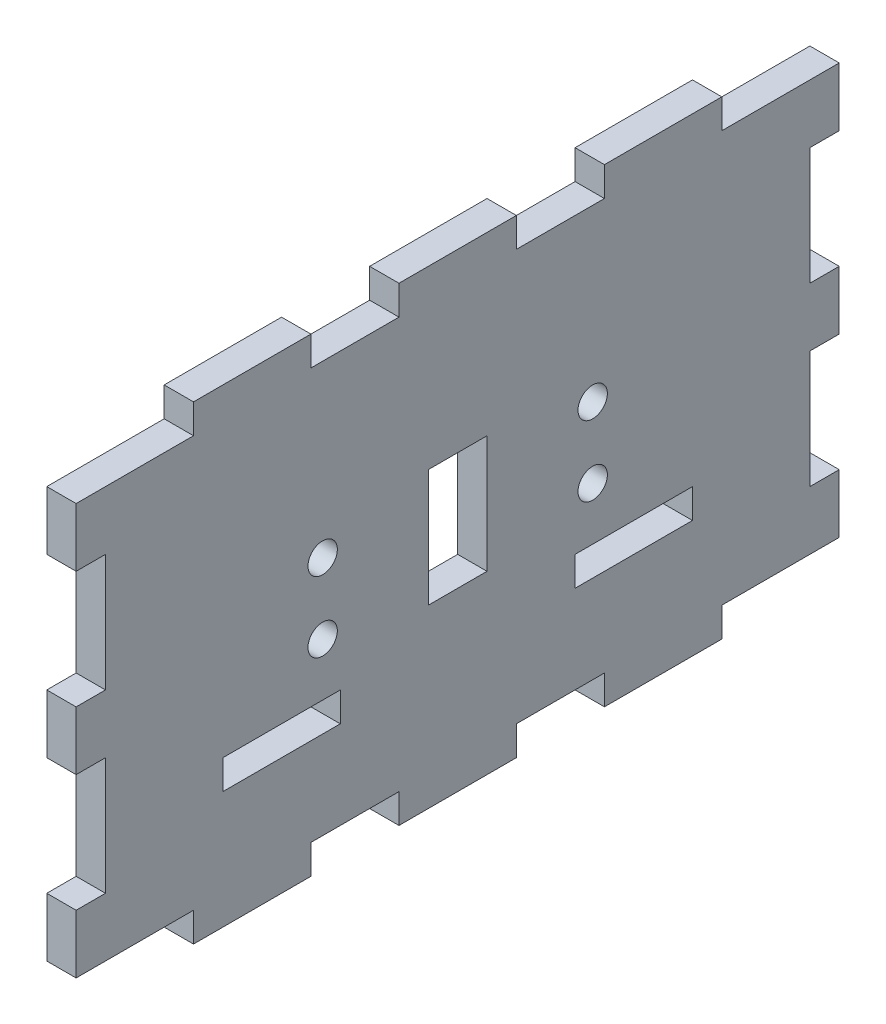
SolidWorks part; units mm, degrees
ref_plane "Front Plane" through (0, 0, 0) normal (0, 0, 1) x (1, 0, 0)
ref_plane "Top Plane" through (0, 0, 0) normal (0, 1, 0) x (1, 0, 0)
ref_plane "Right Plane" through (0, 0, 0) normal (1, 0, 0) x (0, 0, -1)
sketch "Sketch1" plane through (0, 0, 0) normal (1, 0, 0) x (0, 0, -1)
  line L0 (-109.8871, 0) -> (84.0492, 0) construction
  line L1 (0, 64.1388) -> (0, -100.6158) construction
  line L2 (-60, 35) -> (-45, 35)
  line L3 (-60, 35) -> (60, 35) construction
  line L4 (-60, 35) -> (-60, -35) construction
  line L5 (-60, -35) -> (60, -35) construction
  line L6 (60, 35) -> (60, -35) construction
  line L7 (-60, 35) -> (60, -35) construction
  line L8 (-60, -35) -> (60, 35) construction
  line L9 (-45, 35) -> (-45, 40)
  line L10 (-45, 40) -> (-25, 40)
  line L11 (-25, 40) -> (-25, 35)
  line L12 (-10, 35) -> (-10, 40)
  line L13 (-10, 40) -> (10, 40)
  line L14 (10, 40) -> (10, 35)
  line L15 (-25, 35) -> (-10, 35)
  line L16 (25, 35) -> (25, 40)
  line L17 (25, 40) -> (45, 40)
  line L18 (45, 40) -> (45, 35)
  line L19 (10, 35) -> (25, 35)
  line L20 (45, -35) -> (60, -35)
  line L21 (10, -35) -> (25, -35)
  line L22 (45, -40) -> (45, -35)
  line L23 (45, 35) -> (60, 35)
  line L24 (60, 40) -> (80, 40) [skipped]
  line L25 (80, 40) -> (80, 35) [skipped]
  line L26 (60, 35) -> (60, 40) [skipped]
  line L27 (25, -40) -> (45, -40)
  line L28 (25, -35) -> (25, -40)
  line L29 (-25, -35) -> (-10, -35)
  line L30 (10, -40) -> (10, -35)
  line L31 (-10, -40) -> (10, -40)
  line L32 (-10, -35) -> (-10, -40)
  line L33 (-25, -40) -> (-25, -35)
  line L34 (-45, -40) -> (-25, -40)
  line L35 (-45, -35) -> (-45, -40)
  line L36 (-60, -35) -> (-45, -35)
  line L37 (-60, 35) -> (-65, 35)
  line L38 (-65, 35) -> (-65, 25)
  line L39 (-65, 25) -> (-60, 25)
  line L40 (-60, 25) -> (-60, 5)
  line L41 (-60, 5) -> (-65, 5)
  line L42 (-65, 5) -> (-65, -5)
  line L43 (-65, -5) -> (-60, -5)
  line L44 (-60, -5) -> (-60, -25)
  line L45 (-60, -25) -> (-65, -25)
  line L46 (-65, -25) -> (-65, -35)
  line L47 (-65, -35) -> (-60, -35)
  line L48 (65, -35) -> (60, -35)
  line L49 (60, 35) -> (65, 35)
  line L50 (65, -25) -> (65, -35)
  line L51 (60, -25) -> (65, -25)
  line L52 (60, -5) -> (60, -25)
  line L53 (65, -5) -> (60, -5)
  line L54 (65, 5) -> (65, -5)
  line L55 (60, 5) -> (65, 5)
  line L56 (60, 25) -> (60, 5)
  line L57 (65, 25) -> (60, 25)
  line L58 (65, 35) -> (65, 25)
  point P5 (0, 0)
  dimension "D1" = 70
  dimension "D2" = 120
  dimension "D3" = 4
extrude "Boss-Extrude1" add sketch "Sketch1" along normal blind 5 contours L58 L49 L23 L18 L17 L16 L19 L14 L13 L12 L15 L11 L10 L9 L2 L37 L38 L39 L40 L41 L42 L43 L44 L45 L46 L47 L36 L35 L34 L33 L29 L32 L31 L30 L21 L28 L27 L22 L20 L48 L50 L51 L52 L53 L54 L55 L56 L57
sketch "Sketch2" plane through (0, 0, 0) normal (1, 0, 0) x (0, 0, -1)
  line L0 (0, 0) -> (39.3291, 0) construction
  line L1 (-5, 10) -> (5, 10)
  line L2 (-5, 10) -> (-5, -10)
  line L3 (-5, -10) -> (5, -10)
  line L4 (5, 10) -> (5, -10)
  line L5 (-5, 10) -> (5, -10) construction
  line L6 (-5, -10) -> (5, 10) construction
  line L7 (0, 0) -> (-48.4922, 0) construction
  line L8 (0, 17.5211) -> (0, -27.1046) construction
  circle A0 centre (23, 6) radius 2.5
  circle A1 centre (23, -6) radius 2.5
  circle A2 centre (-23, -6) radius 2.5
  circle A3 centre (-23, 6) radius 2.5
  point P0 (0, 0)
  dimension "D3" = 5
  dimension "D1" = 20
  dimension "D2" = 10
  dimension "D4" = 6
  dimension "D5" = 18
extrude "Cut-Extrude1" cut sketch "Sketch2" along normal up to surface (5 mm away) up to face at (5, 0, 0)
sketch "Sketch3" plane through (5, 0, 0) normal (1, 0, 0) x (0, 0, -1)
  line L0 (-60, -5) -> (-60, -25) construction
  line L1 (-60, -20) -> (60, -20) construction
  line L2 (60, -5) -> (60, -25) construction
  line L3 (-25, -35) -> (-10, -35) construction
  line L4 (0, -3.8143) -> (0, -32.5252) construction
  line L5 (20, -20) -> (20, -15)
  line L6 (20, -15) -> (40, -15)
  line L7 (40, -15) -> (40, -20)
  line L8 (40, -20) -> (20, -20)
  line L9 (-40, -20) -> (-20, -20)
  line L10 (-40, -15) -> (-40, -20)
  line L11 (-20, -15) -> (-40, -15)
  line L12 (-20, -20) -> (-20, -15)
  dimension "D1" = 120
  dimension "D2" = 15
  dimension "D3" = 5
  dimension "D4" = 20
  dimension "D5" = 20
extrude "Cut-Extrude2" cut sketch "Sketch3" against normal up to surface (5 mm away) up to face at (0, 6, -25.5)
